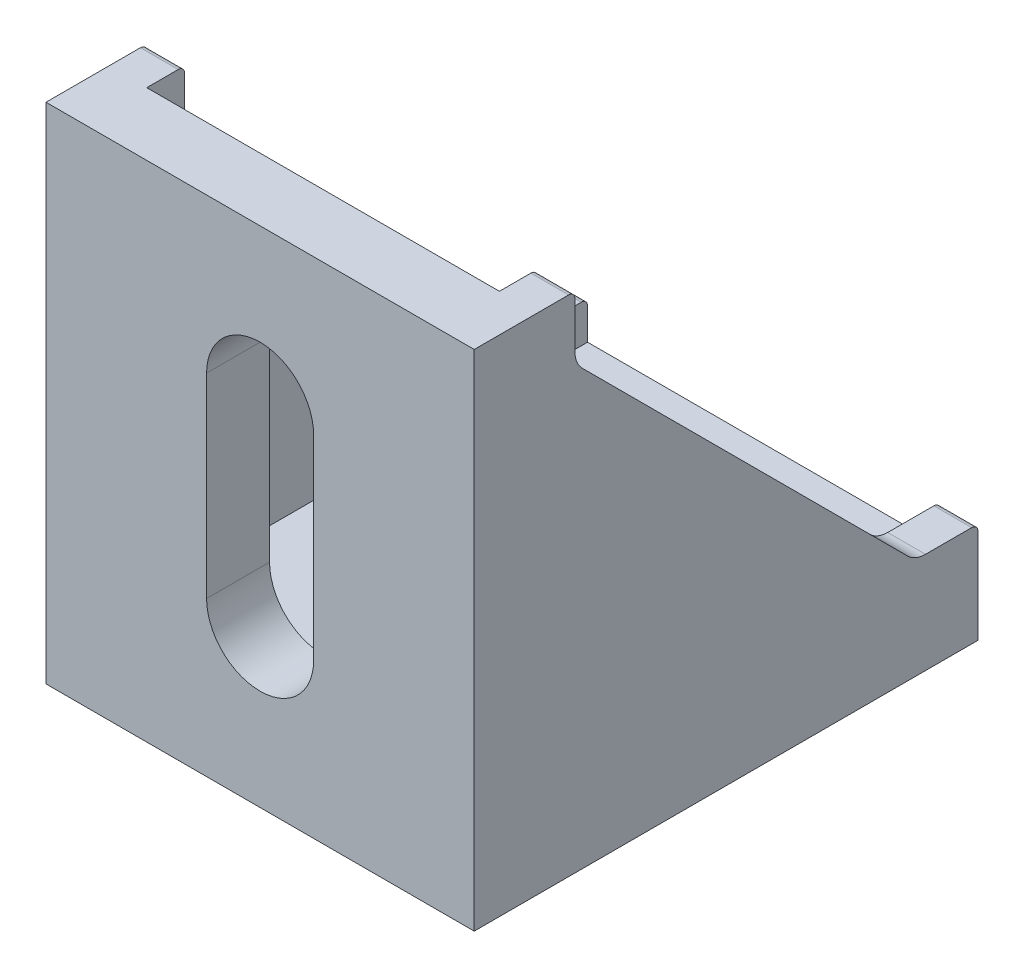
SolidWorks part; units mm, degrees
ref_plane "Front Plane" through (0, 0, 0) normal (0, 0, 1) x (1, 0, 0)
ref_plane "Top Plane" through (0, 0, 0) normal (0, 1, 0) x (1, 0, 0)
ref_plane "Right Plane" through (0, 0, 0) normal (1, 0, 0) x (0, 0, -1)
sketch "Sketch1" plane through (0, 0, 0) normal (1, 0, 0) x (0, 0, -1)
  line L1 (-20, -20) -> (20, -20)
  line L2 (-20, -20) -> (-20, 20)
  line L3 (-20, 20) -> (-12.5, 20)
  line L4 (20, -20) -> (20, -12.5)
  line L6 (-20, -12) -> (20, -12) construction
  line L7 (15.8284, -12) -> (19.5, -12)
  line L10 (-11.4142, 14.4142) -> (14.4142, -11.4142)
  line L11 (-12, 15.8284) -> (-12, 19.5)
  arc A0 (-11.4142, 14.4142) -> (-12, 15.8284) centre (-10, 15.8284) cw
  arc A1 (14.4142, -11.4142) -> (15.8284, -12) centre (15.8284, -10) ccw
  arc A2 (-12.5, 20) -> (-12, 19.5) centre (-12.5, 19.5) cw
  arc A3 (19.5, -12) -> (20, -12.5) centre (19.5, -12.5) cw
  point P0 (0, 0)
  dimension "D1" = 2
  dimension "D2" = 2
  dimension "D3" = 0.5
  dimension "D4" = 0.5
extrude "Boss-Extrude1" add sketch "Sketch1" along normal blind 34
sketch "Sketch2" plane through (0, 20, 0) normal (0, 1, 0) x (1, 0, 0)
  line L0 (31, -15) -> (3, -15)
  line L2 (3, -15) -> (3, -12)
  line L7 (3, -12) -> (3, 23.6125)
  line L8 (31, -15) -> (31, -12)
  line L12 (3, 23.6125) -> (31, 23.6125)
  line L13 (31, 23.6125) -> (31, -12)
extrude "Cut-Extrude1" cut sketch "Sketch2" against normal blind 35
sketch "Sketch4" plane through (0, -20, 0) normal (0, -1, 0) x (1, 0, 0)
  line L5 (12.75, 7.75) -> (12.75, -7.75)
  line L8 (21.25, 7.75) -> (21.25, -7.75)
  arc A0 (21.25, 7.75) -> (12.75, 7.75) centre (17, 7.75) ccw
  arc A1 (21.25, -7.75) -> (12.75, -7.75) centre (17, -7.75) cw
extrude "Cut-Extrude2" cut sketch "Sketch4" against normal blind 35
sketch "Sketch5" plane through (0, 0, 20) normal (0, 0, 1) x (1, 0, 0)
  line L9 (12.75, 7.75) -> (12.75, -7.75)
  line L10 (21.25, 7.75) -> (21.25, -7.75)
  arc A0 (21.25, 7.75) -> (12.75, 7.75) centre (17, 7.75) ccw
  arc A1 (21.25, -7.75) -> (12.75, -7.75) centre (17, -7.75) cw
extrude "Cut-Extrude3" cut sketch "Sketch5" against normal blind 35
